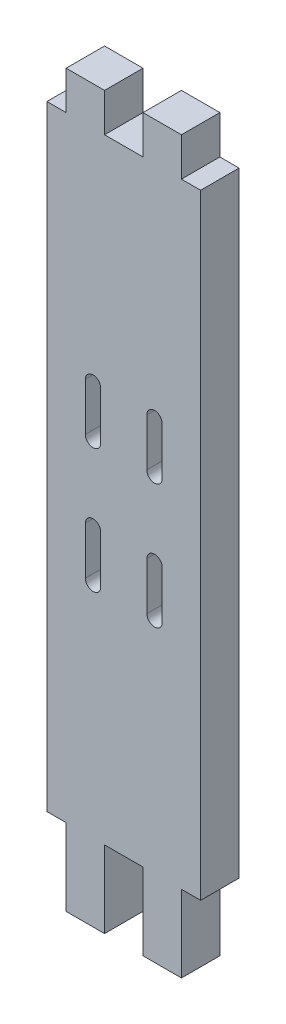
SolidWorks part; units mm, degrees
ref_plane "Front Plane" through (0, 0, 0) normal (0, 0, 1) x (1, 0, 0)
ref_plane "Top Plane" through (0, 0, 0) normal (0, 1, 0) x (1, 0, 0)
ref_plane "Right Plane" through (0, 0, 0) normal (1, 0, 0) x (0, 0, -1)
sketch "Sketch1" plane through (0, 0, 0) normal (0, 0, 1) x (1, 0, 0)
  line L0 (-7.5, 40) -> (-7.5, 45)
  line L1 (-10, -40) -> (-7.5, -40)
  line L2 (-10, -40) -> (-10, 40)
  line L3 (-10, 40) -> (-7.5, 40)
  line L4 (10, -40) -> (10, 40)
  line L5 (-10, -40) -> (10, 40) construction
  line L6 (-10, 40) -> (10, -40) construction
  line L7 (-7.5, 45) -> (-2.5, 45)
  line L8 (-2.5, 45) -> (-2.5, 40)
  line L9 (2.5, 40) -> (2.5, 45)
  line L10 (2.5, 45) -> (7.5, 45)
  line L11 (7.5, 45) -> (7.5, 40)
  line L12 (-2.5, 40) -> (2.5, 40)
  line L13 (7.5, 40) -> (10, 40)
  line L14 (-2.5, -40) -> (2.5, -40)
  line L16 (-7.5, -40) -> (-7.5, -45)
  line L20 (2.5, -40) -> (2.5, -45)
  line L23 (7.5, -40) -> (10, -40)
  line L24 (-7.5, -45) -> (-7.5, -50)
  line L25 (-7.5, -50) -> (-2.5, -50)
  line L26 (-2.5, -50) -> (-2.5, -40)
  line L27 (2.5, -45) -> (2.5, -50)
  line L28 (2.5, -50) -> (7.5, -50)
  line L29 (7.5, -50) -> (7.5, -40)
  line L30 (0, 0) -> (0, 44.2491) construction
  line L31 (0, 0) -> (41.6146, 0) construction
  line L32 (4, -11.2) -> (4, -5) construction
  line L35 (3, -11.2) -> (3, -5)
  line L38 (5, -11.2) -> (5, -5)
  line L41 (4, 11.2) -> (4, 5) construction
  line L44 (3, 11.2) -> (3, 5)
  line L51 (5, 11.2) -> (5, 5)
  line L52 (-4, 11.2) -> (-4, 5) construction
  line L53 (-3, 11.2) -> (-3, 5)
  line L54 (-5, 11.2) -> (-5, 5)
  line L55 (-4, -11.2) -> (-4, -5) construction
  line L56 (-3, -11.2) -> (-3, -5)
  line L57 (-5, -11.2) -> (-5, -5)
  arc A29 (3, -11.2) -> (5, -11.2) centre (4, -11.2) ccw
  arc A30 (5, -5) -> (3, -5) centre (4, -5) ccw
  arc A33 (3, 11.2) -> (5, 11.2) centre (4, 11.2) cw
  arc A34 (5, 5) -> (3, 5) centre (4, 5) cw
  arc A35 (-3, 11.2) -> (-5, 11.2) centre (-4, 11.2) ccw
  arc A36 (-5, 5) -> (-3, 5) centre (-4, 5) ccw
  arc A37 (-3, -11.2) -> (-5, -11.2) centre (-4, -11.2) cw
  arc A38 (-5, -5) -> (-3, -5) centre (-4, -5) cw
  point P0 (0, 0)
  point P29 (4, -8.1)
  point P36 (4, 8.1)
  point P41 (0, 0)
  point P42 (0, 0)
  point P45 (-4, 8.1)
  point P52 (-4, -8.1)
  dimension "D8" = 1
  dimension "D9" = 6.2
  dimension "D1" = 5
  dimension "D2" = 5
  dimension "D3" = 20
  dimension "D4" = 5
  dimension "D5" = 80
  dimension "D6" = 5
  dimension "D7" = 10
  dimension "D10" = 4
  dimension "D11" = 8.1
extrude "Boss-Extrude1" add sketch "Sketch1" along normal blind 5
